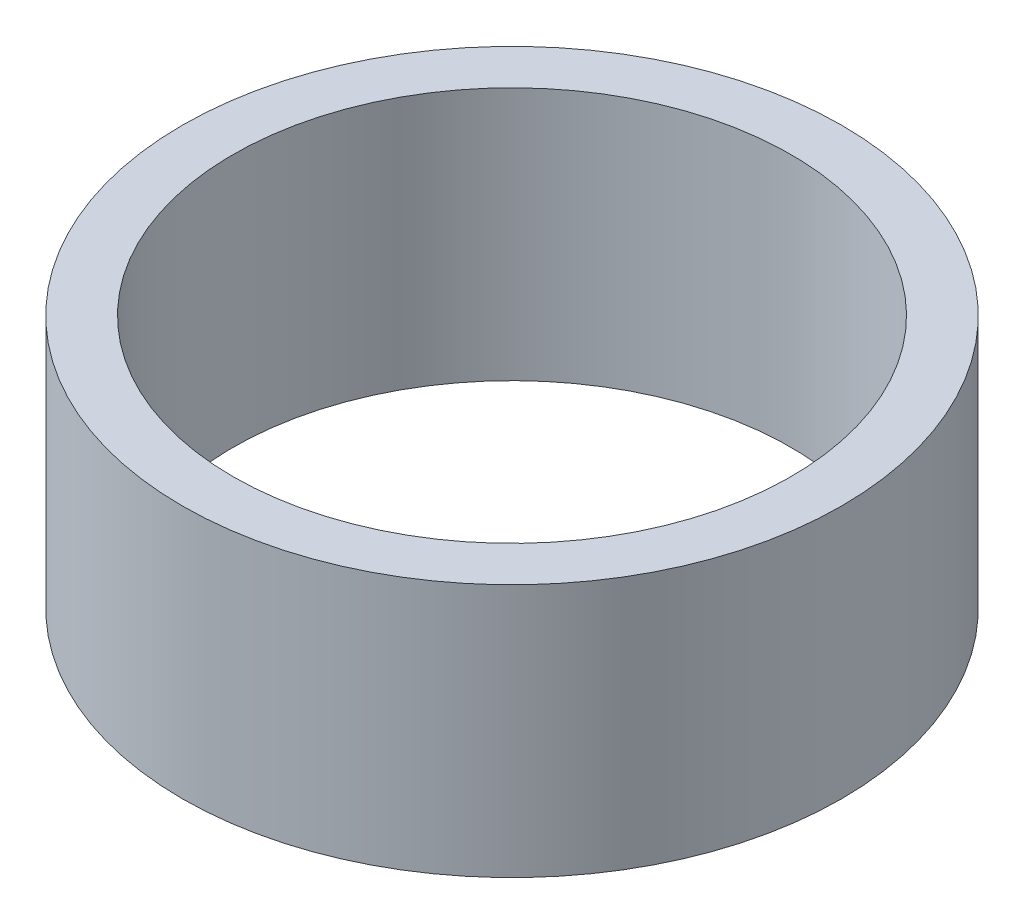
SolidWorks part; units mm, degrees
ref_plane "Front View" through (0, 0, 0) normal (0, 0, 1) x (1, 0, 0)
ref_plane "Upper View" through (0, 0, 0) normal (0, 1, 0) x (1, 0, 0)
ref_plane "Right View" through (0, 0, 0) normal (1, 0, 0) x (0, 0, -1)
sketch "Sketch1" plane through (0, 0, 0) normal (0, 1, 0) x (1, 0, 0)
  circle A0 centre (0, 0) radius 6.5
  circle A1 centre (0, 0) radius 5.5
extrude "Boss-Extrude1" add sketch "Sketch1" along normal blind 5
